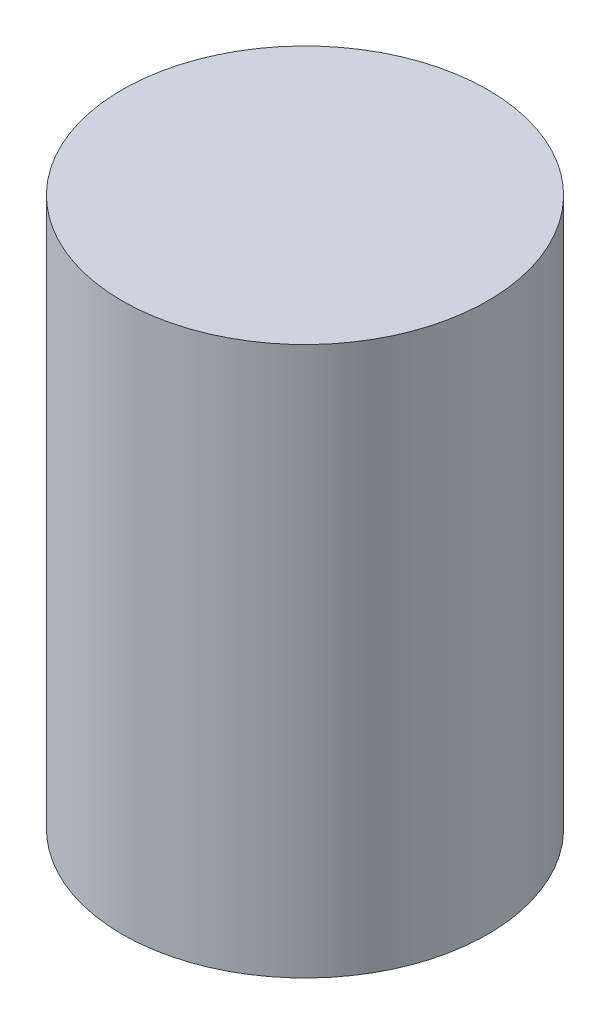
SolidWorks part; units mm, degrees
ref_plane "Front Plane" through (0, 0, 0) normal (0, 0, 1) x (1, 0, 0)
ref_plane "Top Plane" through (0, 0, 0) normal (0, 1, 0) x (1, 0, 0)
ref_plane "Right Plane" through (0, 0, 0) normal (1, 0, 0) x (0, 0, -1)
sketch "Sketch1" plane through (0, 0, 0) normal (0, 1, 0) x (1, 0, 0)
  circle A0 centre (0, 0) radius 20
  dimension "D1" = 40
extrude "Boss-Extrude1" add sketch "Sketch1" along normal blind 60
